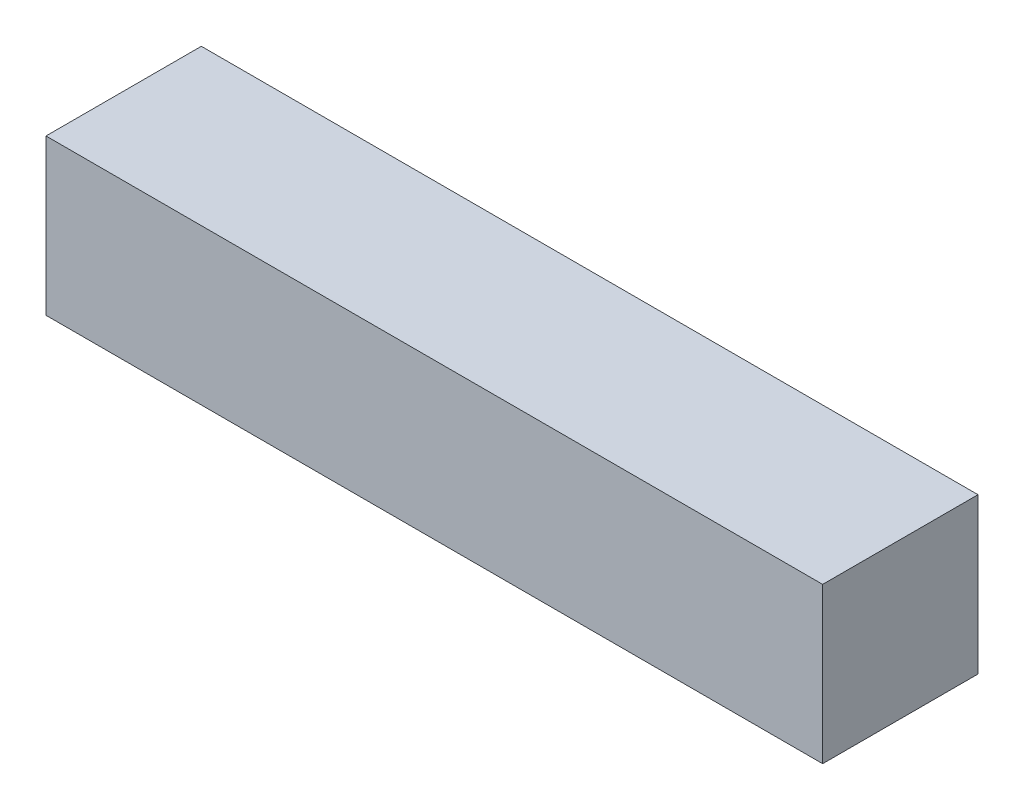
SolidWorks part; units mm, degrees
ref_plane "Front Plane" through (0, 0, 0) normal (0, 0, 1) x (1, 0, 0)
ref_plane "Top Plane" through (0, 0, 0) normal (0, 1, 0) x (1, 0, 0)
ref_plane "Right Plane" through (0, 0, 0) normal (1, 0, 0) x (0, 0, -1)
sketch "Sketch1" plane through (0, 0, 0) normal (0, 0, 1) x (1, 0, 0)
  line L1 (-50, 10) -> (50, 10)
  line L2 (-50, 10) -> (-50, -10)
  line L3 (-50, -10) -> (50, -10)
  line L4 (50, 10) -> (50, -10)
  line L5 (-50, 10) -> (50, -10) construction
  line L6 (-50, -10) -> (50, 10) construction
  point P0 (0, 0)
  point P6 (0, 0)
  point P7 (0, 0)
  dimension "D1" = 100
  dimension "D2" = 20
extrude "Boss-Extrude1" add sketch "Sketch1" along normal blind 20
